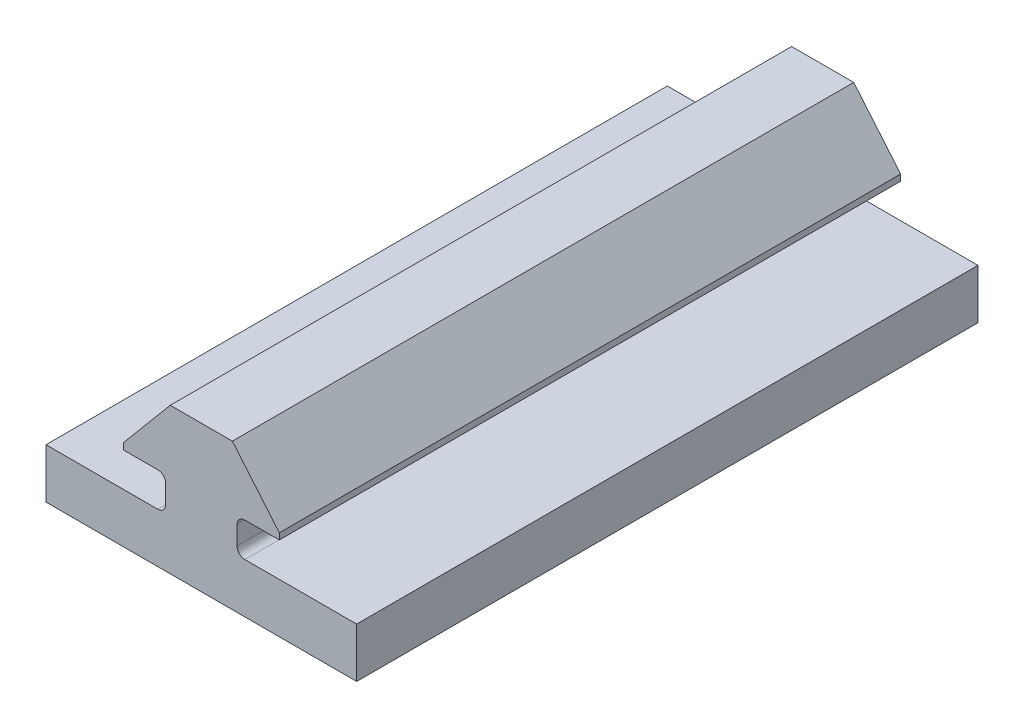
SolidWorks part; units mm, degrees
ref_plane "Front Plane" through (0, 0, 0) normal (0, 0, 1) x (1, 0, 0)
ref_plane "Top Plane" through (0, 0, 0) normal (0, 1, 0) x (1, 0, 0)
ref_plane "Right Plane" through (0, 0, 0) normal (1, 0, 0) x (0, 0, -1)
ref_plane "Plane1" through (0, 0, -3683) normal (0, 0, -1) x (-1, 0, 0)
sketch "Sketch1" plane through (0, 0, -3683) normal (0, 0, -1) x (-1, 0, 0)
  line L0 (12.7, 4.064) -> (3.556, 4.064)
  line L1 (2.921, 4.699) -> (2.921, 6.223)
  line L2 (3.556, 6.858) -> (6.3764, 6.858)
  line L3 (6.3764, 6.858) -> (6.3764, 7.366)
  line L4 (6.3764, 7.366) -> (2.54, 11.938)
  line L5 (2.54, 11.938) -> (-2.54, 11.938)
  line L6 (-2.54, 11.938) -> (-6.3764, 7.366)
  line L7 (-6.3764, 7.366) -> (-6.3764, 6.858)
  line L8 (-6.3764, 6.858) -> (-3.556, 6.858)
  line L9 (-2.921, 6.223) -> (-2.921, 4.699)
  line L10 (-3.556, 4.064) -> (-12.7, 4.064)
  line L11 (-12.7, 4.064) -> (-12.7, 0)
  line L12 (-12.7, 0) -> (12.7, 0)
  line L13 (12.7, 0) -> (12.7, 4.064)
  arc A0 (3.556, 4.064) -> (2.921, 4.699) centre (3.556, 4.699) cw
  arc A1 (2.921, 6.223) -> (3.556, 6.858) centre (3.556, 6.223) cw
  arc A2 (-3.556, 6.858) -> (-2.921, 6.223) centre (-3.556, 6.223) cw
  arc A3 (-2.921, 4.699) -> (-3.556, 4.064) centre (-3.556, 4.699) cw
extrude "Boss-Extrude6" add sketch "Sketch1" along normal blind 50.8
